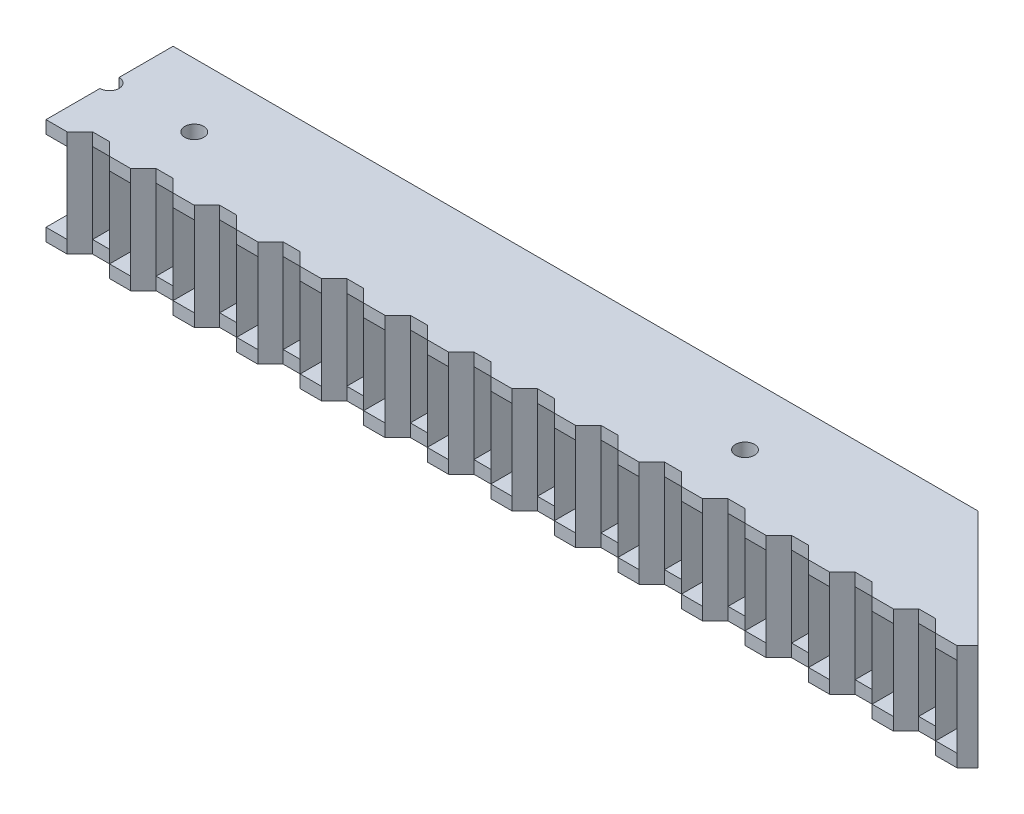
SolidWorks part; units mm, degrees
ref_plane "Front Plane" through (0, 0, 0) normal (0, 0, 1) x (1, 0, 0)
ref_plane "Top Plane" through (0, 0, 0) normal (0, 1, 0) x (1, 0, 0)
ref_plane "Right Plane" through (0, 0, 0) normal (1, 0, 0) x (0, 0, -1)
sketch "Sketch3" plane through (0, 0, 0) normal (0, 1, 0) x (1, 0, 0)
  line L0 (0, 0) -> (358.2319, 0) construction
  line L1 (0, 0) -> (220, 0)
  line L2 (220, 0) -> (190, 30)
  line L3 (190, 30) -> (0, 30)
  line L4 (0, 30) -> (0, 0)
  circle A0 centre (0, 15) radius 2.25
  circle A1 centre (20, 15) radius 2.25
  circle A2 centre (150, 15) radius 2.25
  dimension "D4" = 4.5
  dimension "D1" = 220
  dimension "D2" = 30
  dimension "D3" = 45
  dimension "D5" = 20
  dimension "D6" = 150
extrude "Boss-Extrude2" add sketch "Sketch3" along normal blind 25 contours A0 L4 L1 L2 L3 A2 A1
sketch "Sketch6" plane through (0, 25, 0) normal (0, 1, 0) x (1, 0, 0)
  line L0 (0, 0) -> (5, 0)
  line L1 (0, 0) -> (220, 0) construction
  line L2 (5, 0) -> (8, 3)
  line L3 (8, 3) -> (12, 3)
  line L4 (12, 3) -> (15, 0)
  line L5 (15, 0) -> (20, 0)
  line L6 (20, 0) -> (23, 3)
  line L7 (27, 3) -> (30, 0)
  line L8 (23, 3) -> (27, 3)
  line L9 (30, 0) -> (35, 0)
  line L10 (35, 0) -> (38, 3)
  line L11 (42, 3) -> (45, 0)
  line L12 (38, 3) -> (42, 3)
  line L13 (45, 0) -> (50, 0)
  line L14 (50, 0) -> (53, 3)
  line L15 (57, 3) -> (60, 0)
  line L16 (53, 3) -> (57, 3)
  line L17 (60, 0) -> (65, 0)
  line L18 (65, 0) -> (68, 3)
  line L19 (72, 3) -> (75, 0)
  line L20 (68, 3) -> (72, 3)
  line L21 (75, 0) -> (80, 0)
  line L22 (80, 0) -> (83, 3)
  line L23 (87, 3) -> (90, 0)
  line L24 (83, 3) -> (87, 3)
  line L25 (90, 0) -> (95, 0)
  line L26 (95, 0) -> (98, 3)
  line L27 (102, 3) -> (105, 0)
  line L28 (98, 3) -> (102, 3)
  line L29 (105, 0) -> (110, 0)
  line L30 (110, 0) -> (113, 3)
  line L31 (117, 3) -> (120, 0)
  line L32 (113, 3) -> (117, 3)
  line L33 (120, 0) -> (125, 0)
  line L34 (125, 0) -> (128, 3)
  line L35 (132, 3) -> (135, 0)
  line L36 (128, 3) -> (132, 3)
  line L37 (135, 0) -> (140, 0)
  line L38 (140, 0) -> (143, 3)
  line L39 (147, 3) -> (150, 0)
  line L40 (143, 3) -> (147, 3)
  line L41 (150, 0) -> (155, 0)
  line L42 (155, 0) -> (158, 3)
  line L43 (162, 3) -> (165, 0)
  line L44 (158, 3) -> (162, 3)
  line L45 (165, 0) -> (170, 0)
  line L46 (170, 0) -> (173, 3)
  line L47 (177, 3) -> (180, 0)
  line L48 (173, 3) -> (177, 3)
  line L49 (180, 0) -> (185, 0)
  line L50 (185, 0) -> (188, 3)
  line L51 (192, 3) -> (195, 0)
  line L52 (188, 3) -> (192, 3)
  line L53 (195, 0) -> (200, 0)
  line L54 (200, 0) -> (203, 3)
  line L55 (207, 3) -> (210, 0)
  line L56 (203, 3) -> (207, 3)
  line L57 (210, 0) -> (215, 0)
  line L58 (215, 0) -> (218, 3)
  line L59 (222, 3) -> (225, 0)
  line L60 (218, 3) -> (222, 3)
  line L61 (0, 0) -> (0, -19.0347)
  line L62 (0, -19.0347) -> (225, -19.0347)
  line L63 (225, -19.0347) -> (225, 0)
  dimension "D1" = 15
  dimension "D2" = 5
  dimension "D4" = 3
extrude "Cut-Extrude2" cut sketch "Sketch6" against normal blind 54
sketch "Sketch7" plane through (0, 0, -3) normal (0, 0, 1) x (1, 0, 0)
  line L0 (8, 0) -> (8, 25) construction
  line L1 (8, 22) -> (12, 22)
  line L2 (8, 22) -> (8, 3)
  line L3 (8, 3) -> (12, 3)
  line L4 (12, 22) -> (12, 3)
  line L5 (12, 0) -> (12, 25) construction
  line L6 (12, 25) -> (8, 25) construction
  line L7 (12, 0) -> (8, 0) construction
  line L8 (23, 22) -> (23, 3)
  line L9 (23, 22) -> (27, 22)
  line L10 (27, 22) -> (27, 3)
  line L11 (23, 3) -> (27, 3)
  line L12 (38, 22) -> (38, 3)
  line L13 (38, 22) -> (42, 22)
  line L14 (42, 22) -> (42, 3)
  line L15 (38, 3) -> (42, 3)
  line L16 (53, 22) -> (53, 3)
  line L17 (53, 22) -> (57, 22)
  line L18 (57, 22) -> (57, 3)
  line L19 (53, 3) -> (57, 3)
  line L20 (68, 22) -> (68, 3)
  line L21 (68, 22) -> (72, 22)
  line L22 (72, 22) -> (72, 3)
  line L23 (68, 3) -> (72, 3)
  line L24 (83, 22) -> (83, 3)
  line L25 (83, 22) -> (87, 22)
  line L26 (87, 22) -> (87, 3)
  line L27 (83, 3) -> (87, 3)
  line L28 (98, 22) -> (98, 3)
  line L29 (98, 22) -> (102, 22)
  line L30 (102, 22) -> (102, 3)
  line L31 (98, 3) -> (102, 3)
  line L32 (113, 22) -> (113, 3)
  line L33 (113, 22) -> (117, 22)
  line L34 (117, 22) -> (117, 3)
  line L35 (113, 3) -> (117, 3)
  line L36 (128, 22) -> (128, 3)
  line L37 (128, 22) -> (132, 22)
  line L38 (132, 22) -> (132, 3)
  line L39 (128, 3) -> (132, 3)
  line L40 (143, 22) -> (143, 3)
  line L41 (143, 22) -> (147, 22)
  line L42 (147, 22) -> (147, 3)
  line L43 (143, 3) -> (147, 3)
  line L44 (158, 22) -> (158, 3)
  line L45 (158, 22) -> (162, 22)
  line L46 (162, 22) -> (162, 3)
  line L47 (158, 3) -> (162, 3)
  line L48 (173, 22) -> (173, 3)
  line L49 (173, 22) -> (177, 22)
  line L50 (177, 22) -> (177, 3)
  line L51 (173, 3) -> (177, 3)
  line L52 (188, 22) -> (188, 3)
  line L53 (188, 22) -> (192, 22)
  line L54 (192, 22) -> (192, 3)
  line L55 (188, 3) -> (192, 3)
  line L56 (203, 22) -> (203, 3)
  line L57 (203, 22) -> (207, 22)
  line L58 (207, 22) -> (207, 3)
  line L59 (203, 3) -> (207, 3)
  line L60 (218, 22) -> (218, 3)
  line L61 (218, 22) -> (222, 22)
  line L62 (222, 22) -> (222, 3)
  line L63 (218, 3) -> (222, 3)
  dimension "D1" = 3
  dimension "D2" = 3
  dimension "D3" = 15
extrude "Cut-Extrude3" cut sketch "Sketch7" against normal blind 54
sketch "Sketch8" plane through (0, 0, 0) normal (0, 0, 1) x (1, 0, 0)
  line L0 (0, 25) -> (0, 0) construction
  line L1 (0, 22) -> (5, 22)
  line L2 (0, 22) -> (0, 3)
  line L3 (0, 3) -> (5, 3)
  line L4 (5, 22) -> (5, 3)
  line L5 (5, 0) -> (5, 25) construction
  line L6 (0, 25) -> (5, 25) construction
  line L7 (0, 0) -> (5, 0) construction
  line L8 (15, 3) -> (20, 3)
  line L9 (20, 22) -> (20, 3)
  line L10 (15, 22) -> (20, 22)
  line L11 (15, 22) -> (15, 3)
  line L12 (30, 3) -> (35, 3)
  line L13 (35, 22) -> (35, 3)
  line L14 (30, 22) -> (35, 22)
  line L15 (30, 22) -> (30, 3)
  line L16 (45, 3) -> (50, 3)
  line L17 (50, 22) -> (50, 3)
  line L18 (45, 22) -> (50, 22)
  line L19 (45, 22) -> (45, 3)
  line L20 (60, 3) -> (65, 3)
  line L21 (65, 22) -> (65, 3)
  line L22 (60, 22) -> (65, 22)
  line L23 (60, 22) -> (60, 3)
  line L24 (75, 3) -> (80, 3)
  line L25 (80, 22) -> (80, 3)
  line L26 (75, 22) -> (80, 22)
  line L27 (75, 22) -> (75, 3)
  line L28 (90, 3) -> (95, 3)
  line L29 (95, 22) -> (95, 3)
  line L30 (90, 22) -> (95, 22)
  line L31 (90, 22) -> (90, 3)
  line L32 (105, 3) -> (110, 3)
  line L33 (110, 22) -> (110, 3)
  line L34 (105, 22) -> (110, 22)
  line L35 (105, 22) -> (105, 3)
  line L36 (120, 3) -> (125, 3)
  line L37 (125, 22) -> (125, 3)
  line L38 (120, 22) -> (125, 22)
  line L39 (120, 22) -> (120, 3)
  line L40 (135, 3) -> (140, 3)
  line L41 (140, 22) -> (140, 3)
  line L42 (135, 22) -> (140, 22)
  line L43 (135, 22) -> (135, 3)
  line L44 (150, 3) -> (155, 3)
  line L45 (155, 22) -> (155, 3)
  line L46 (150, 22) -> (155, 22)
  line L47 (150, 22) -> (150, 3)
  line L48 (165, 3) -> (170, 3)
  line L49 (170, 22) -> (170, 3)
  line L50 (165, 22) -> (170, 22)
  line L51 (165, 22) -> (165, 3)
  line L52 (180, 3) -> (185, 3)
  line L53 (185, 22) -> (185, 3)
  line L54 (180, 22) -> (185, 22)
  line L55 (180, 22) -> (180, 3)
  line L56 (195, 3) -> (200, 3)
  line L57 (200, 22) -> (200, 3)
  line L58 (195, 22) -> (200, 22)
  line L59 (195, 22) -> (195, 3)
  line L60 (210, 3) -> (215, 3)
  line L61 (215, 22) -> (215, 3)
  line L62 (210, 22) -> (215, 22)
  line L63 (210, 22) -> (210, 3)
  dimension "D1" = 3
  dimension "D2" = 3
  dimension "D3" = 15
extrude "Cut-Extrude4" cut sketch "Sketch8" against normal blind 54
sketch "Sketch9" plane through (0, 25, 0) normal (0, 1, 0) x (1, 0, 0)
  line L0 (0, 22.5) -> (0, 17.25)
  line L1 (0, 30) -> (0, 17.25) construction
  line L2 (0, 12.75) -> (0, 7.5)
  circle A0 centre (20, 15) radius 2.25
  circle A1 centre (20, 15) radius 7.5
  arc A2 (0, 12.75) -> (0, 17.25) centre (0, 15) ccw
  arc A3 (0, 7.5) -> (0, 22.5) centre (0, 15) ccw
  circle A4 centre (150, 15) radius 2.25
  circle A5 centre (150, 15) radius 7.5
  dimension "D1" = 15
extrude "Boss-Extrude3" add sketch "Sketch9" against normal up to surface (25 mm away) up to face at (150, 0, -12.75)
